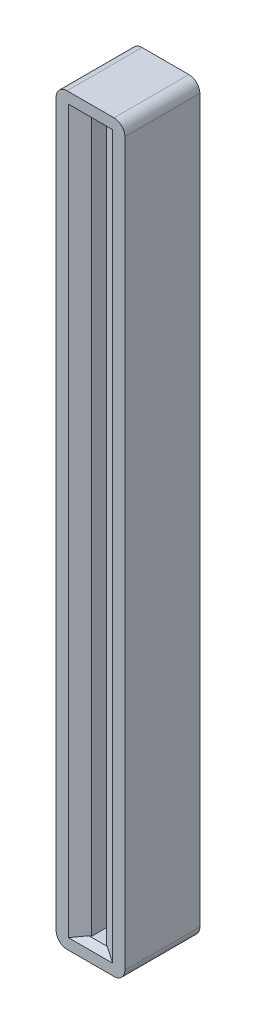
SolidWorks part; units mm, degrees
ref_plane "Front" through (0, 0, 0) normal (0, 0, 1) x (1, 0, 0)
ref_plane "Top" through (0, 0, 0) normal (0, 1, 0) x (1, 0, 0)
ref_plane "Right" through (0, 0, 0) normal (1, 0, 0) x (0, 0, -1)
sketch "Sketch1" plane through (0, 0, 0) normal (0, 0, 1) x (1, 0, 0)
  line L0 (0, -58.1025) -> (0, 58.1025) construction
  line L1 (-44.603, 0) -> (44.603, 0) construction
  line L2 (-5.0165, 61.9125) -> (5.0165, 61.9125)
  line L3 (5.0165, 61.9125) -> (5.0165, -61.9125)
  line L4 (-5.0165, 61.9125) -> (-5.0165, -61.9125)
  line L5 (-5.0165, -61.9125) -> (5.0165, -61.9125)
  point P0 (0, -61.9125)
  point P9 (0, 61.9125)
  point P11 (-5.0165, 0)
  point P12 (5.0165, 0)
  point P13 (0, 0)
  dimension "D1" = 123.825
  dimension "D2" = 10.033
  dimension "D3" = 116.205
sketch "Sketch2" plane through (0, 0, 0) normal (0, 0, 1) x (1, 0, 0)
  line L2 (-5.0165, 54.2925) -> (5.0165, 54.2925)
  line L3 (5.0165, 54.2925) -> (5.0165, -54.2925)
  line L4 (0, 54.2925) -> (0, 0) construction
  line L5 (0, 0) -> (5.0165, 0) construction
  line L6 (-5.0165, 54.2925) -> (-5.0165, -54.2925)
  line L7 (-5.0165, -54.2925) -> (5.0165, -54.2925)
  point P9 (-5.0165, 0)
  dimension "D1" = 10.033
  dimension "D2" = 108.585
extrude "Extrude2" add sketch "Sketch2" along normal blind 10.9474
fillet "Fillet1" radius 1.5875 4 edges at (5.0165, 54.2925, 5.4737) (5.0165, -54.2925, 5.4737) (-5.0165, -54.2925, 5.4737) (-5.0165, 54.2925, 5.4737)
sketch "Sketch7" plane through (0, 0, 10.9474) normal (0, 0, 1) x (1, 0, 0)
  line L0 (1.0795, -52.07) -> (1.0795, 52.07)
  line L1 (1.0795, 52.07) -> (-1.0795, 52.07)
  line L2 (0, 0) -> (2.159, 0) construction
  line L9 (-1.0795, -52.07) -> (-1.0795, 52.07)
  line L10 (1.0795, -52.07) -> (-1.0795, -52.07)
  line L11 (0, 0) -> (0, 53.4946) construction
  point P0 (1.0795, 0)
  point P5 (0, 52.07)
  point P8 (-1.0795, 0)
  dimension "D1" = 104.14
  dimension "D2" = 2.159
extrude "Cut-Extrude2" cut sketch "Sketch7" against normal blind 6.731
chamfer "Chamfer1" distance 2.159 angle 30 2 edges at (1.0795, 0, 10.9474) (-1.0795, 0, 10.9474)
chamfer "Chamfer2" distance 0.635 angle 60 2 edges at (0, 52.07, 10.9474) (0, -52.07, 10.9474)
